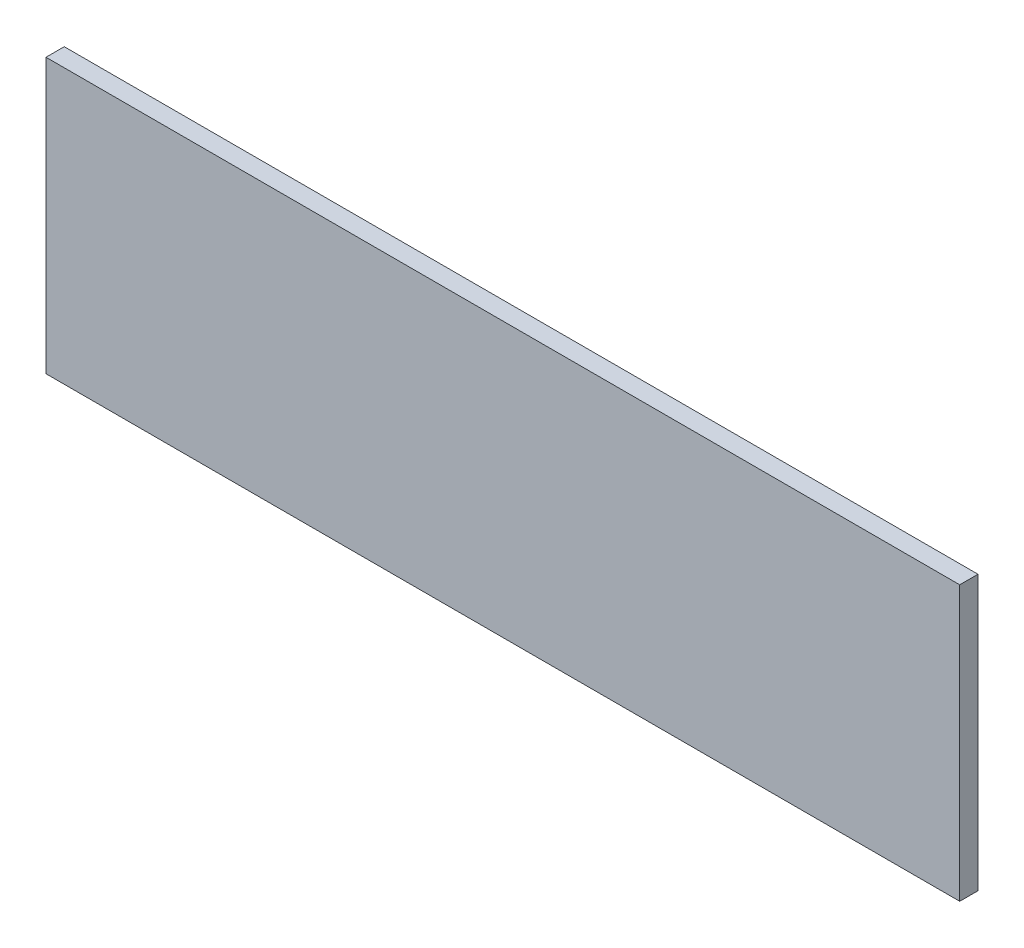
SolidWorks part; units mm, degrees
material "Acrylic (Medium-high impact)"
ref_plane "Front Plane" through (0, 0, 0) normal (0, 0, 1) x (1, 0, 0)
ref_plane "Top Plane" through (0, 0, 0) normal (0, 1, 0) x (1, 0, 0)
ref_plane "Right Plane" through (0, 0, 0) normal (1, 0, 0) x (0, 0, -1)
sketch "Sketch1" plane through (0, 0, 0) normal (0, 0, 1) x (1, 0, 0)
  line L0 (-177.9793, -55.9585) -> (322.0207, -55.9585)
  line L1 (322.0207, -55.9585) -> (322.0207, 94.0415)
  line L2 (322.0207, 94.0415) -> (-177.9793, 94.0415)
  line L3 (-177.9793, 94.0415) -> (-177.9793, -55.9585)
  dimension "D1" = 150
  dimension "D2" = 500
extrude "Boss-Extrude1" add sketch "Sketch1" along normal blind 10
